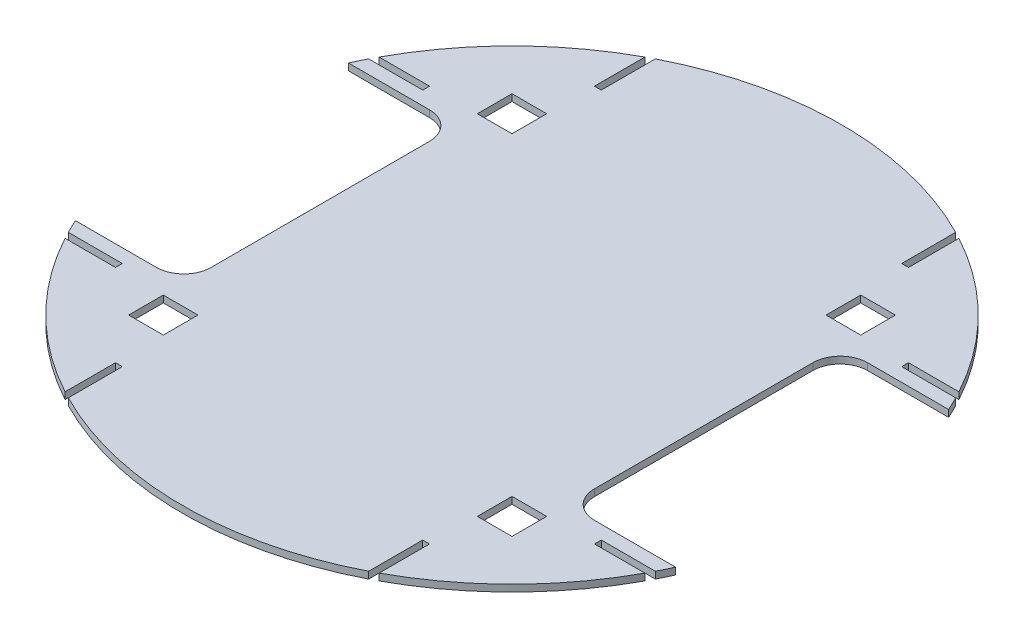
SolidWorks part; units mm, degrees
ref_plane "Front Plane" through (0, 0, 0) normal (0, 0, 1) x (1, 0, 0)
ref_plane "Top Plane" through (0, 0, 0) normal (0, 1, 0) x (1, 0, 0)
ref_plane "Right Plane" through (0, 0, 0) normal (1, 0, 0) x (0, 0, -1)
sketch "Sketch1" plane through (0, 0, 0) normal (0, 1, 0) x (1, 0, 0)
  line L0 (140.4, 115) -> (115, 115)
  line L1 (-140.4, 140.4) -> (140.4, 140.4) construction
  line L2 (-140.4, 140.4) -> (-140.4, -140.4) construction
  line L3 (-140.4, -140.4) -> (140.4, -140.4) construction
  line L4 (140.4, 140.4) -> (140.4, -140.4) construction
  line L5 (0, -140.4) -> (0, 140.4) construction
  line L6 (-140.4, 0) -> (140.4, 0) construction
  line L7 (-140.4, 140.4) -> (-115, 140.4)
  line L8 (-140.4, 140.4) -> (-140.4, 115)
  line L9 (-140.4, 115) -> (-115, 115)
  line L10 (-115, 140.4) -> (-115, 115)
  line L11 (115, 140.4) -> (115, 115)
  line L12 (140.4, 140.4) -> (115, 140.4)
  line L13 (140.4, 140.4) -> (140.4, 115)
  line L14 (140.4, -140.4) -> (140.4, -115)
  line L15 (140.4, -115) -> (115, -115)
  line L16 (115, -140.4) -> (115, -115)
  line L17 (140.4, -140.4) -> (115, -140.4)
  line L18 (-140.4, -115) -> (-115, -115)
  line L19 (-115, -140.4) -> (-115, -115)
  line L20 (-140.4, -140.4) -> (-115, -140.4)
  line L21 (-140.4, -140.4) -> (-140.4, -115)
  line L22 (-219.7903, 100) -> (-160.4, 100)
  line L23 (-140.4, 80) -> (-140.4, -80)
  line L24 (-160.4, -100) -> (-219.7903, -100)
  line L25 (160.4, 100) -> (219.7903, 100)
  line L26 (160.4, -100) -> (219.7903, -100)
  line L27 (140.4, 80) -> (140.4, -80)
  line L28 (115, 175.4) -> (110, 175.4)
  line L29 (-115, 175.4) -> (-110, 175.4)
  line L30 (-115, 175.4) -> (-115, 212.327)
  line L31 (110, 175.4) -> (110, 214.9599)
  line L32 (-110, 175.4) -> (-110, 214.9599)
  line L33 (-175.4, 115) -> (-212.327, 115)
  line L34 (-175.4, 115) -> (-175.4, 110)
  line L35 (-175.4, 110) -> (-214.9599, 110)
  line L36 (115, 175.4) -> (115, 212.327)
  line L37 (175.4, 115) -> (175.4, 110)
  line L38 (175.4, 115) -> (212.327, 115)
  line L39 (175.4, 110) -> (214.9599, 110)
  line L40 (175.4, -110) -> (214.9599, -110)
  line L41 (175.4, -115) -> (175.4, -110)
  line L42 (175.4, -115) -> (212.327, -115)
  line L43 (110, -175.4) -> (110, -214.9599)
  line L44 (115, -175.4) -> (115, -212.327)
  line L45 (115, -175.4) -> (110, -175.4)
  line L46 (-115, -175.4) -> (-110, -175.4)
  line L47 (-110, -175.4) -> (-110, -214.9599)
  line L48 (-115, -175.4) -> (-115, -212.327)
  line L49 (-175.4, -115) -> (-175.4, -110)
  line L50 (-175.4, -110) -> (-214.9599, -110)
  line L51 (-175.4, -115) -> (-212.327, -115)
  arc A0 (-219.7903, -100) -> (-214.9599, -110) centre (0, 0) ccw
  arc A1 (219.7903, 100) -> (214.9599, 110) centre (0, 0) ccw
  arc A2 (-214.9599, 110) -> (-219.7903, 100) centre (0, 0) ccw
  arc A3 (-115, 212.327) -> (-212.327, 115) centre (0, 0) ccw
  arc A4 (110, 214.9599) -> (-110, 214.9599) centre (0, 0) ccw
  arc A5 (212.327, 115) -> (115, 212.327) centre (0, 0) ccw
  arc A6 (214.9599, -110) -> (219.7903, -100) centre (0, 0) ccw
  arc A7 (115, -212.327) -> (212.327, -115) centre (0, 0) ccw
  arc A8 (-110, -214.9599) -> (110, -214.9599) centre (0, 0) ccw
  arc A9 (-212.327, -115) -> (-115, -212.327) centre (0, 0) ccw
  arc A10 (160.4, -100) -> (140.4, -80) centre (160.4, -80) cw
  arc A11 (160.4, 100) -> (140.4, 80) centre (160.4, 80) ccw
  arc A12 (-140.4, -80) -> (-160.4, -100) centre (-160.4, -80) cw
  arc A13 (-160.4, 100) -> (-140.4, 80) centre (-160.4, 80) cw
  point P59 (140.4, -100)
  point P62 (140.4, 100)
  point P65 (-140.4, -100)
  point P68 (-140.4, 100)
  dimension "D1" = 482.94
  dimension "D11" = 20
  dimension "D2" = 280.8
  dimension "D3" = 25.4
  dimension "D4" = 15
  dimension "D5" = 15
  dimension "D6" = 15
  dimension "D7" = 5
  dimension "D8" = 35
  dimension "D9" = 35
  dimension "D10" = 5
extrude "Boss-Extrude1" add sketch "Sketch1" along normal blind 5
